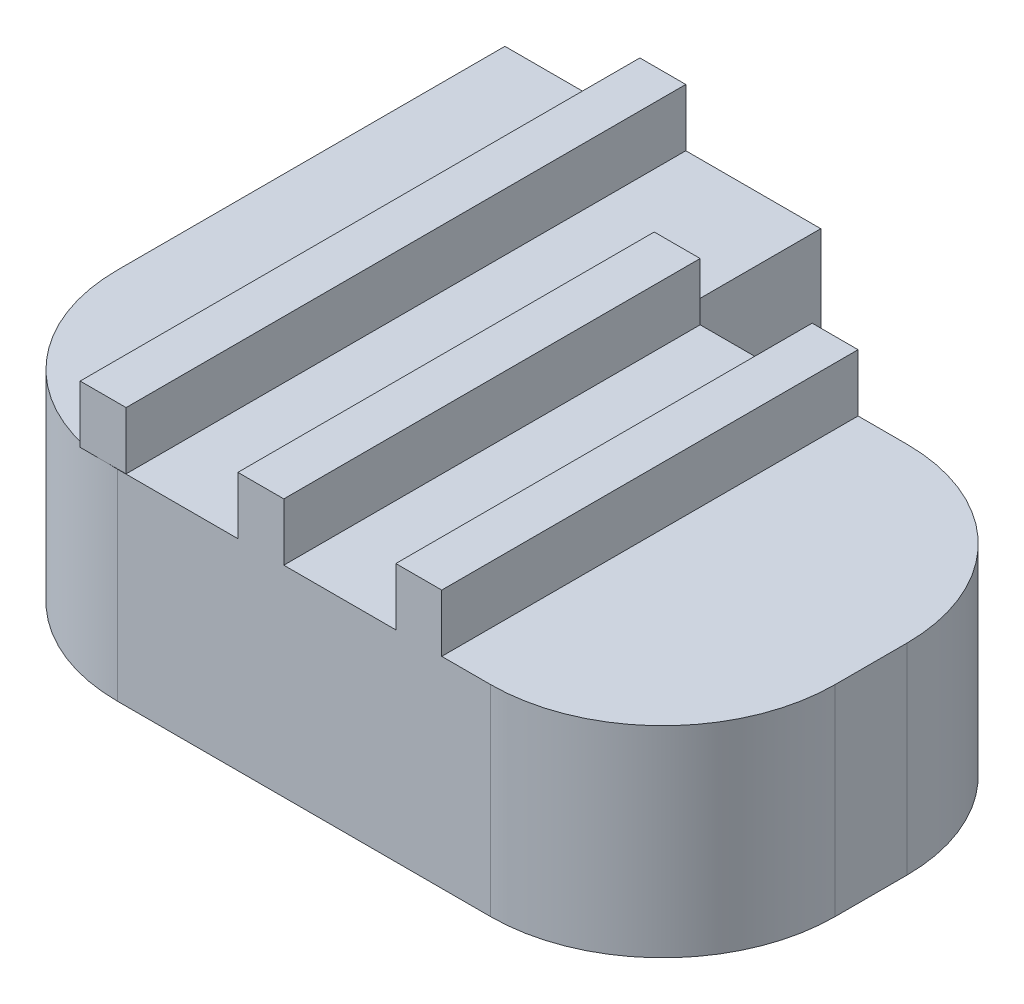
SolidWorks part; units mm, degrees
ref_plane "前视基准面" through (0, 0, 0) normal (0, 0, 1) x (1, 0, 0)
ref_plane "上视基准面" through (0, 0, 0) normal (0, 1, 0) x (1, 0, 0)
ref_plane "右视基准面" through (0, 0, 0) normal (1, 0, 0) x (0, 0, -1)
other "Configuration Table"
sketch "草图1" plane through (0, 0, 0) normal (0, 1, 0) x (1, 0, 0)
  line L1 (0, 0) -> (12.5, 0)
  line L2 (0, 0) -> (0, 7.25)
  line L3 (0, 7.25) -> (12.5, 7.25)
  line L4 (12.5, 0) -> (12.5, 7.25)
  line L5 (0, 0) -> (12.5, 7.25) construction
  line L6 (0, 7.25) -> (12.5, 0) construction
  point P4 (6.25, 3.625)
  dimension "D1" = 7.25
  dimension "D2" = 12.5
extrude "凸台-拉伸1" add sketch "草图1" along normal blind 3.5
fillet "圆角1" radius 3 3 edges at (12.5, 1.75, -7.25) (0, 1.75, 0) (12.5, 1.75, 0)
sketch "草图2" plane through (0, 3.5, 0) normal (0, 1, 0) x (1, 0, 0)
  line L1 (0, 7.25) -> (5.5, 7.25)
  line L2 (0, 7.25) -> (0, 9.75)
  line L3 (0, 9.75) -> (5.5, 9.75)
  line L4 (5.5, 7.25) -> (5.5, 9.75)
  line L5 (0, 7.25) -> (5.5, 9.75) construction
  line L6 (0, 9.75) -> (5.5, 7.25) construction
  point P4 (2.75, 8.5)
  point P6 (5.3261, 7.5)
  dimension "D1" = 2.5
  dimension "D2" = 5.5
extrude "凸台-拉伸2" add sketch "草图2" against normal up to surface (3.5 mm away)
sketch "草图3" plane through (0, 3.5, 0) normal (0, 1, 0) x (1, 0, 0)
  line L0 (5.5, 9.75) -> (0, 9.75) construction
  line L1 (2.35, 9.75) -> (3.15, 9.75)
  line L2 (2.35, 9.75) -> (2.35, 0.0038)
  line L3 (2.35, 0.0038) -> (3.15, 0.0038)
  line L4 (3.15, 9.75) -> (3.15, 0.0038)
  line L5 (2.35, 9.75) -> (3.15, 0.0038) construction
  line L6 (2.35, 0.0038) -> (3.15, 9.75) construction
  line L7 (9.5, 7.25) -> (5.5, 7.25) construction
  line L8 (5.9, 7.25) -> (5.1, 7.25)
  line L9 (5.9, 7.25) -> (5.9, 0)
  line L10 (5.9, 0) -> (5.1, 0)
  line L11 (5.1, 7.25) -> (5.1, 0)
  line L12 (5.9, 7.25) -> (5.1, 0) construction
  line L13 (5.9, 0) -> (5.1, 7.25) construction
  line L14 (3, 0) -> (9.5, 0) construction
  line L15 (0, 9.75) -> (0, 3) construction
  line L16 (8.65, 7.25) -> (7.85, 7.25)
  line L17 (8.65, 7.25) -> (8.65, 0)
  line L18 (8.65, 0) -> (7.85, 0)
  line L19 (7.85, 7.25) -> (7.85, 0)
  line L20 (8.65, 7.25) -> (7.85, 0) construction
  line L21 (8.65, 0) -> (7.85, 7.25) construction
  arc A0 (0, 3) -> (3, 0) centre (3, 3) ccw construction
  point P4 (2.75, 4.8769)
  point P14 (5.5, 3.625)
  point P23 (8.25, 3.625)
  dimension "D1" = 0.8
  dimension "D2" = 2.75
  dimension "D3" = 5.5
  dimension "D4" = 8.25
extrude "凸台-拉伸3" add sketch "草图3" along normal blind 1
sketch "草图6" plane through (0, 0, 0) normal (0, -1, 0) x (1, 0, 0)
  line L5 (6.365, -4.75) -> (6.365, -5.25)
  line L6 (7.365, -5.25) -> (7.365, -4.75)
  line L7 (6.365, -4.75) -> (6.365, -5.25)
  line L8 (7.365, -5.25) -> (7.365, -4.75)
  line L11 (4.615, -5.25) -> (4.615, -4.75)
  line L12 (3.615, -4.75) -> (3.615, -5.25)
  line L13 (9.115, -4.75) -> (9.115, -5.25)
  line L14 (10.115, -5.25) -> (10.115, -4.75)
  line L15 (9.115, -4.75) -> (9.115, -5.25)
  line L16 (10.115, -5.25) -> (10.115, -4.75)
  line L17 (4.615, -5.25) -> (4.615, -4.75)
  line L18 (3.615, -4.75) -> (3.615, -5.25)
  line L23 (0.865, -4.75) -> (0.865, -5.25)
  line L24 (1.865, -5.25) -> (1.865, -4.75)
  line L25 (0.865, -4.75) -> (0.865, -5.25)
  line L26 (1.865, -5.25) -> (1.865, -4.75)
  arc A6 (7.365, -4.75) -> (6.365, -4.75) centre (6.865, -4.75) ccw
  arc A7 (6.365, -5.25) -> (7.365, -5.25) centre (6.865, -5.25) ccw
  arc A8 (7.365, -4.75) -> (6.365, -4.75) centre (6.865, -4.75) ccw
  arc A9 (6.365, -5.25) -> (7.365, -5.25) centre (6.865, -5.25) ccw
  arc A13 (10.115, -4.75) -> (9.115, -4.75) centre (9.615, -4.75) ccw
  arc A14 (9.115, -5.25) -> (10.115, -5.25) centre (9.615, -5.25) ccw
  arc A15 (10.115, -4.75) -> (9.115, -4.75) centre (9.615, -4.75) ccw
  arc A16 (9.115, -5.25) -> (10.115, -5.25) centre (9.615, -5.25) ccw
  arc A17 (4.615, -4.75) -> (3.615, -4.75) centre (4.115, -4.75) ccw
  arc A18 (3.615, -5.25) -> (4.615, -5.25) centre (4.115, -5.25) ccw
  arc A20 (4.615, -4.75) -> (3.615, -4.75) centre (4.115, -4.75) ccw
  arc A21 (3.615, -5.25) -> (4.615, -5.25) centre (4.115, -5.25) ccw
  arc A28 (1.865, -4.75) -> (0.865, -4.75) centre (1.365, -4.75) ccw
  arc A29 (0.865, -5.25) -> (1.865, -5.25) centre (1.365, -5.25) ccw
  arc A30 (1.865, -4.75) -> (0.865, -4.75) centre (1.365, -4.75) ccw
  arc A31 (0.865, -5.25) -> (1.865, -5.25) centre (1.365, -5.25) ccw
  dimension "D1" = 0.2
  dimension "D2" = 0.2
  dimension "D3" = 0.2
  dimension "D4" = 0.2
extrude "凸台-拉伸4" add sketch "草图6" along normal blind 1
